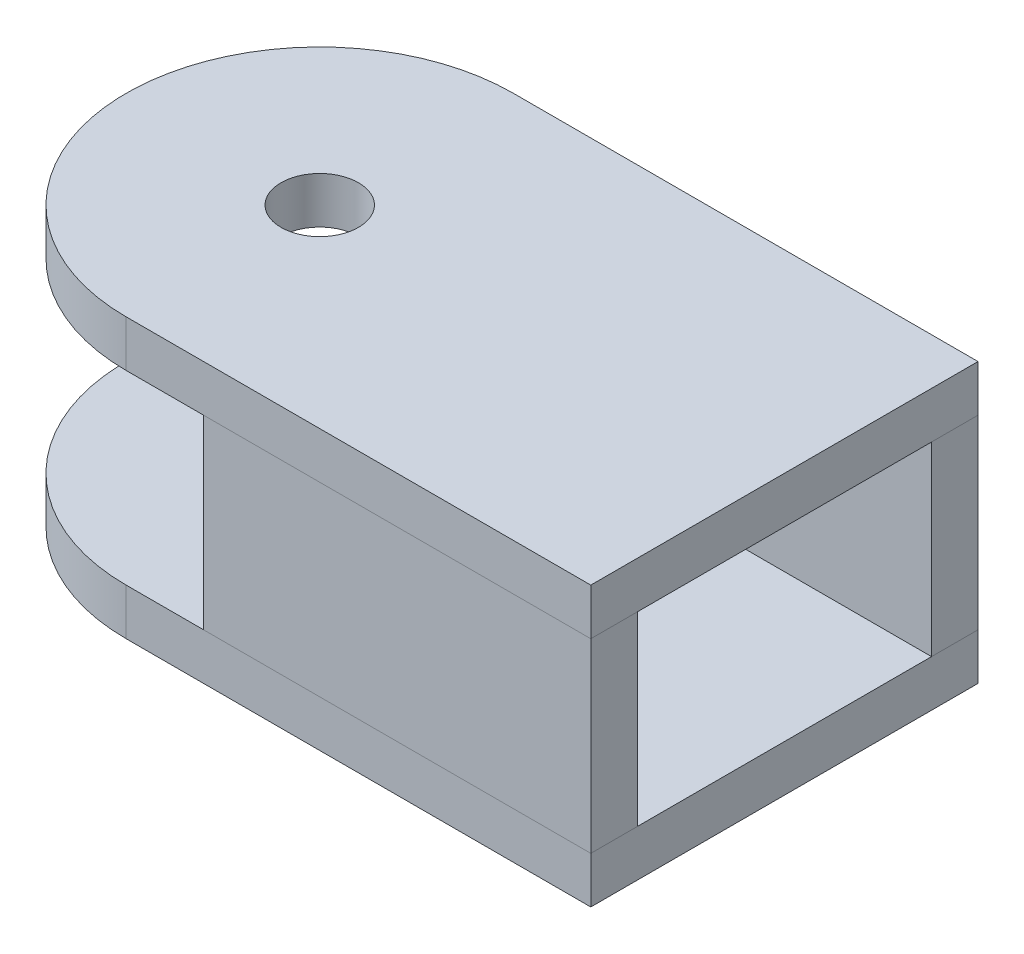
SolidWorks part; units mm, degrees
material "Acrylic (Medium-high impact)"
ref_plane "Front Plane" through (0, 0, 0) normal (0, 0, 1) x (1, 0, 0)
ref_plane "Top Plane" through (0, 0, 0) normal (0, 1, 0) x (1, 0, 0)
ref_plane "Right Plane" through (0, 0, 0) normal (1, 0, 0) x (0, 0, -1)
sketch "Sketch1" plane through (0, 0, 0) normal (0, 1, 0) x (1, 0, 0)
  line L1 (-30, -25) -> (30, -25)
  line L3 (-30, 25) -> (30, 25)
  line L4 (30, -25) -> (30, 25)
  line L5 (-30, -25) -> (30, 25) construction
  line L6 (-30, 25) -> (30, -25) construction
  arc A0 (-30, 25) -> (-30, -25) centre (-30, 0) ccw
  circle A1 centre (-30, 0) radius 5
  point P0 (0, 0)
  dimension "D1" = 10
  dimension "D2" = 25
  dimension "D3" = 60
extrude "Boss-Extrude1" add sketch "Sketch1" along normal mid plane 36
sketch "Sketch2" plane through (0, 0, 0) normal (0, 0, 1) x (1, 0, 0)
  line L0 (-55, 18) -> (-55, -18) construction
  line L1 (-55, 12) -> (30, 12)
  line L2 (-55, 12) -> (-55, -12)
  line L3 (-55, -12) -> (30, -12)
  line L4 (30, 12) -> (30, -12)
  line L5 (30, 18) -> (30, -18) construction
  line L6 (-30, -18) -> (30, -18) construction
  line L7 (-55, 0) -> (0, 0) construction
  dimension "D1" = 6
extrude "Cut-Extrude1" cut sketch "Sketch2" against normal through all and the other way through all
sketch "Sketch3" plane through (0, -12, 0) normal (0, 1, 0) x (1, 0, 0)
  line L1 (30, 25) -> (-20, 25)
  line L2 (30, 25) -> (30, 19)
  line L3 (30, 19) -> (-20, 19)
  line L4 (-20, 25) -> (-20, 19)
  line L5 (30, -25) -> (-20, -25)
  line L6 (30, -25) -> (30, -19)
  line L7 (30, -19) -> (-20, -19)
  line L8 (-20, -25) -> (-20, -19)
  dimension "D1" = 6
  dimension "D2" = 50
extrude "Boss-Extrude2" add sketch "Sketch3" along normal up to next separate body
